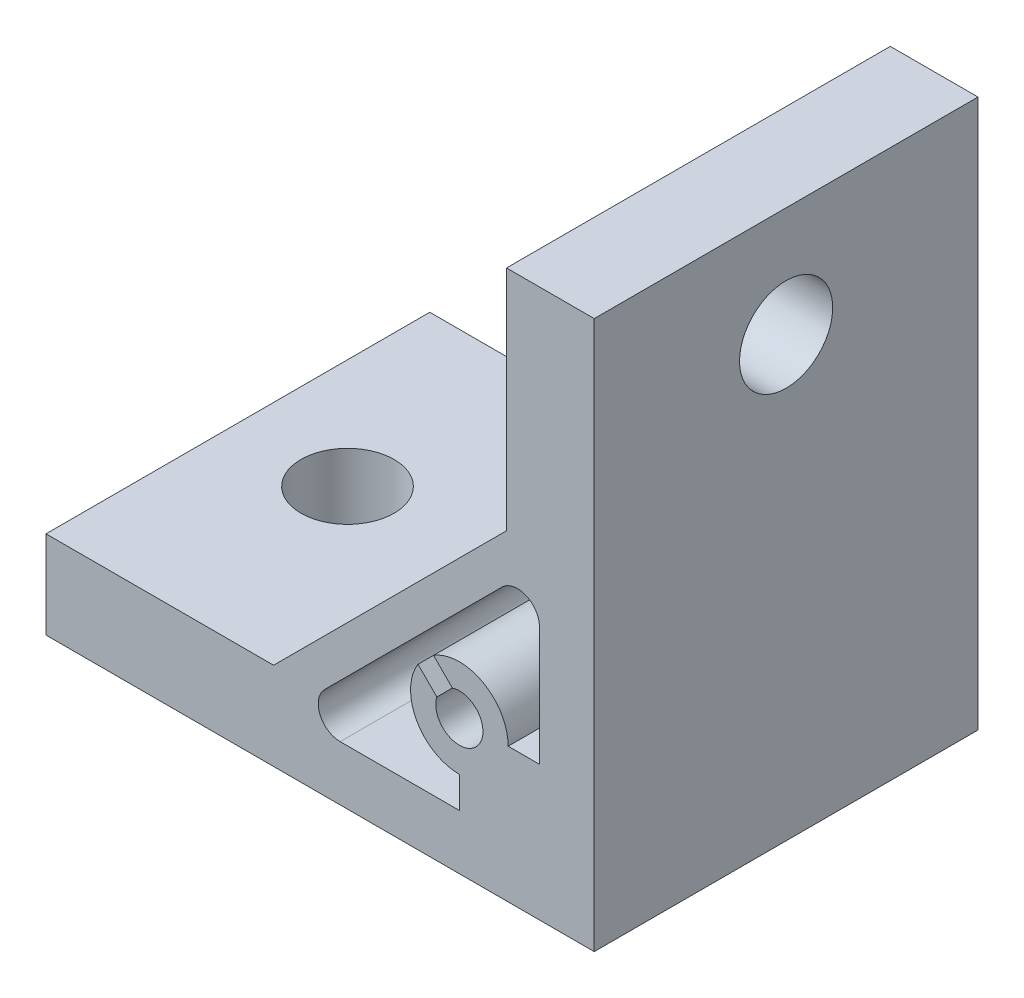
SolidWorks part; units mm, degrees
ref_plane "前视基准面" through (0, 0, 0) normal (0, 0, 1) x (1, 0, 0)
ref_plane "上视基准面" through (0, 0, 0) normal (0, 1, 0) x (1, 0, 0)
ref_plane "右视基准面" through (0, 0, 0) normal (1, 0, 0) x (0, 0, -1)
sketch "草图1" plane through (0, 0, 0) normal (0, 0, 1) x (1, 0, 0)
  line B0 (0, 0) -> (50, 0)
  line B1 (50, 0) -> (50, 50)
  line B2 (0, 8) -> (20.7574, 8)
  line B3 (42, 29.2426) -> (42, 50)
  line B4 (0, 8) -> (0, 0)
  line B5 (42, 50) -> (50, 50)
  line B6 (37.0613, 14.3529) -> (35.341, 16.0733)
  line B7 (35.6471, 12.9387) -> (33.9267, 14.659)
  line B8 (25.4142, 8.4142) -> (41.5858, 24.5858)
  line B9 (20.7574, 8) -> (42, 29.2426)
  line B10 (26.8284, 5) -> (37.7, 5)
  line B11 (45, 23.1716) -> (45, 12.3)
  line B12 (37.7, 5) -> (37.7, 7.85)
  line B13 (42.15, 12.3) -> (45, 12.3)
  arc B14 (33.9267, 14.659) -> (37.7, 7.85) centre (37.7, 12.3) ccw
  arc B15 (42.15, 12.3) -> (35.341, 16.0733) centre (37.7, 12.3) ccw
  arc B16 (35.6471, 12.9387) -> (37.0613, 14.3529) centre (37.7, 12.3) ccw
  arc B17 (25.4142, 8.4142) -> (26.8284, 5) centre (26.8284, 7) ccw
  arc B18 (45, 23.1716) -> (41.5858, 24.5858) centre (43, 23.1716) ccw
sketch_block_instance "A$C19004297-1"
sketch_block "A$C19004297"
extrude "凸台-拉伸1" add sketch "草图1" along normal mid plane 35
sketch "草图3" plane through (0, 8, 0) normal (0, 1, 0) x (1, 0, 0)
  line L0 (0, -17.5) -> (0, 17.5) construction
  circle A0 centre (10, 0) radius 4.25
  dimension "D1" = 10
extrude "切除-拉伸1" cut sketch "草图3" against normal through all
sketch "草图4" plane through (6.3787, -6.3787, 0) normal (-0.7071, 0.7071, 0) x (0, 0, 1)
  line L0 (-17.5, 35.3553) -> (17.5, 35.3553) construction
  line L1 (-17.5, 50.3762) -> (-17.5, 20.3345) construction
  line L2 (17.5, 50.3762) -> (17.5, 20.3345) construction
ref_plane "基准面2" through (25, 25, 0) normal (0.7071, 0.7071, 0) x (0, 0, -1)
mirror "镜向1" about plane through (25, 25, 0) normal (0.7071, 0.7071, 0) of "切除-拉伸1"
